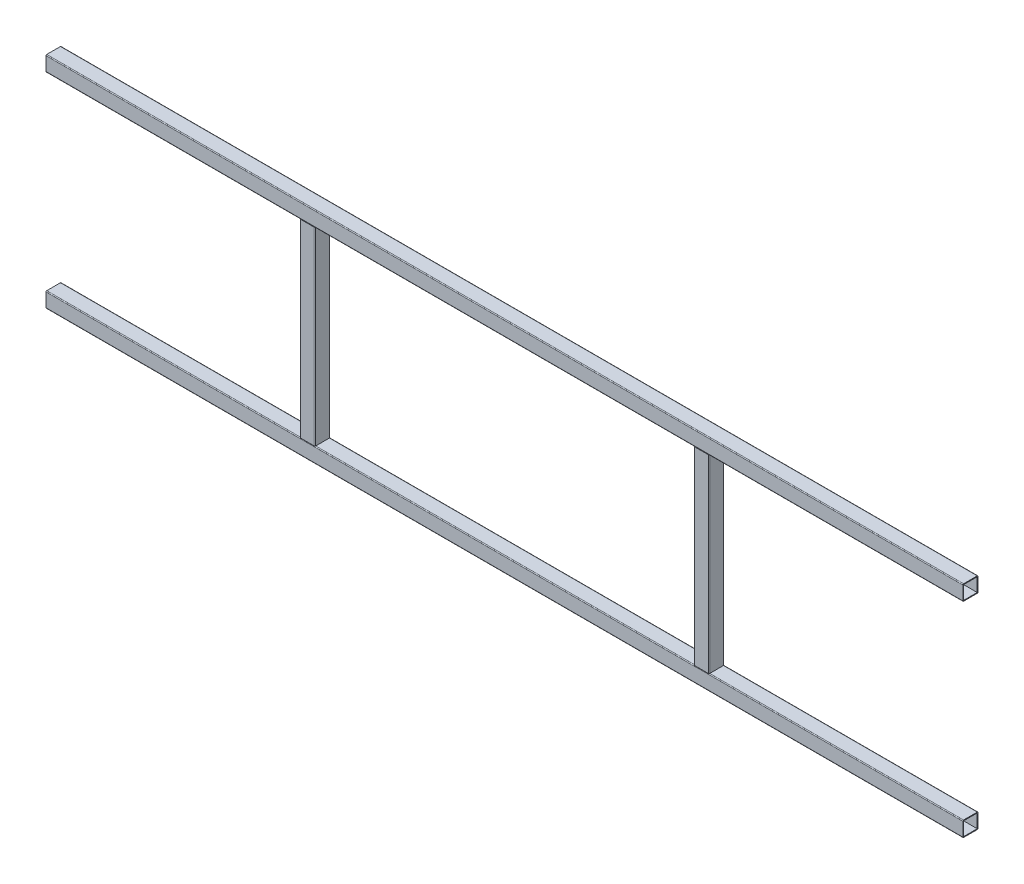
SolidWorks part; units mm, degrees
material "Простая углеродистая сталь"
ref_plane "Спереди" through (0, 0, 0) normal (0, 0, 1) x (1, 0, 0)
ref_plane "Сверху" through (0, 0, 0) normal (0, 1, 0) x (1, 0, 0)
ref_plane "Справа" through (0, 0, 0) normal (1, 0, 0) x (0, 0, -1)
sketch "Эскиз1" plane through (0, 0, 0) normal (0, 0, 1) x (1, 0, 0)
  line L0 (0, 0) -> (4840, 0)
  line L1 (0, -1080) -> (4840, -1080)
  line L2 (2420, 0) -> (2420, -968.4213) construction
  line L4 (1380, 0) -> (1380, -1080)
  line L5 (3460, 0) -> (3460, -1080)
  dimension "D1" = 4840
  dimension "D2" = 1080
  dimension "D4" = 2080
other "Квадратная труба гост 8639-82 _80 X 80 X 4.0(1)"
ref_plane "Плоскость1" through (0, 0, 0) normal (1, 0, 0) x (0, 1, 0)
sketch "Sketch1" plane through (0, 0, 0) normal (1, 0, 0) x (0, 1, 0)
  line L0 (-35.999, -36) -> (35.999, -36)
  line L1 (-36, -35.999) -> (-36, 35.999)
  line L2 (35.999, 36) -> (-35.999, 36)
  line L3 (36, 35.999) -> (36, -35.999)
  line L4 (-35.999, -40) -> (35.999, -40)
  line L5 (-40, -35.999) -> (-40, 35.999)
  line L6 (35.999, 40) -> (-35.999, 40)
  line L7 (40, 35.999) -> (40, -35.999)
  arc A0 (40, 35.999) -> (35.999, 40) centre (35.999, 35.999) ccw
  arc A1 (35.999, -40) -> (40, -35.999) centre (35.999, -35.999) ccw
  arc A2 (-40, -35.999) -> (-35.999, -40) centre (-35.999, -35.999) ccw
  arc A3 (-35.999, 40) -> (-40, 35.999) centre (-35.999, 35.999) ccw
  arc A4 (-35.999, 36) -> (-36, 35.999) centre (-35.999, 35.999) ccw
  arc A5 (36, 35.999) -> (35.999, 36) centre (35.999, 35.999) ccw
  arc A6 (35.999, -36) -> (36, -35.999) centre (35.999, -35.999) ccw
  arc A7 (-36, -35.999) -> (-35.999, -36) centre (-35.999, -35.999) ccw
  point P0 (-40, 0)
  point P1 (40, 0)
  point P2 (0, 40)
  point P3 (0, -40)
  point P4 (0, 0)
  point P5 (-40, -40)
  point P6 (40, -40)
  point P7 (40, 40)
  point P8 (-40, 40)
  point P33 (0, 0)
  dimension "D1" = 4.001
  dimension "Thickness" = 4
  dimension "V_leg" = 80
equation "\"D1@Sketch1\" = \"Thickness@Sketch1\"+0.001"
